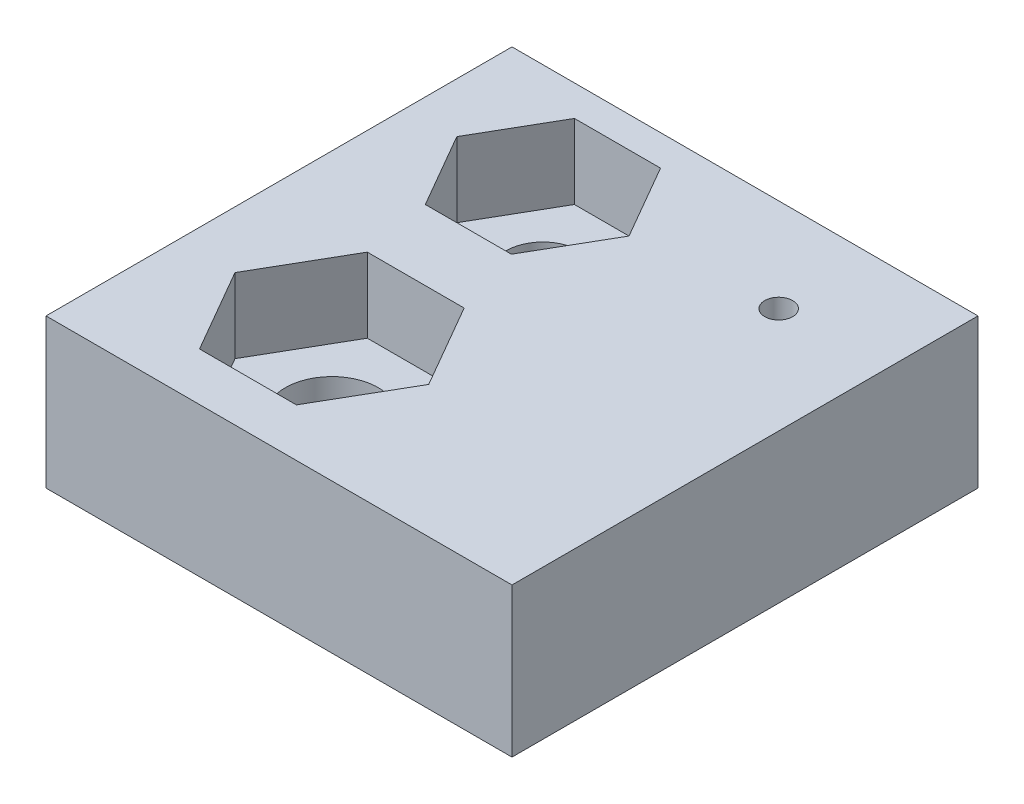
SolidWorks part; units mm, degrees
ref_plane "Front Plane" through (0, 0, 0) normal (0, 0, 1) x (1, 0, 0)
ref_plane "Top Plane" through (0, 0, 0) normal (0, 1, 0) x (1, 0, 0)
ref_plane "Right Plane" through (0, 0, 0) normal (1, 0, 0) x (0, 0, -1)
sketch "Sketch1" plane through (0, 0, 0) normal (0, 1, 0) x (1, 0, 0)
  line L1 (-12.5, -12.5) -> (12.5, -12.5)
  line L2 (-12.5, -12.5) -> (-12.5, 12.5)
  line L3 (-12.5, 12.5) -> (12.5, 12.5)
  line L4 (12.5, -12.5) -> (12.5, 12.5)
  line L5 (-12.5, -12.5) -> (12.5, 12.5) construction
  line L6 (-12.5, 12.5) -> (12.5, -12.5) construction
  point P0 (0, 0)
  dimension "D1" = 25
  dimension "D2" = 25
extrude "Boss-Extrude1" add sketch "Sketch1" along normal blind 8
sketch "Sketch2" plane through (0, 8, 0) normal (0, 1, 0) x (1, 0, 0)
  circle A0 centre (-5.1912, 6.85) radius 2
  circle A1 centre (6.8147, 7.4919) radius 0.75
  circle A2 centre (-4.2474, -5.4178) radius 2.5
  point P4 (-13.0466, 7.2118)
  point P7 (-13.0466, 7.4919)
  point P8 (6.8147, 7.4919)
  point P9 (-5.6821, 7.4919)
  point P10 (-4.2474, -5.4178)
  dimension "D1" = 1.5
  dimension "4" = 4
  dimension "D2" = 5
extrude "Cut-Extrude1" cut sketch "Sketch2" against normal blind 8
sketch "Sketch3" plane through (0, 8, 0) normal (0, 1, 0) x (1, 0, 0)
  line L1 (-0.5724, 6.85) -> (-2.8818, 10.85)
  line L2 (-2.8818, 10.85) -> (-7.5006, 10.85)
  line L3 (-7.5006, 10.85) -> (-9.8101, 6.85)
  line L4 (-9.8101, 6.85) -> (-7.5006, 2.85)
  line L5 (-7.5006, 2.85) -> (-2.8818, 2.85)
  line L6 (-2.8818, 2.85) -> (-0.5724, 6.85)
  line L7 (0.9488, -5.4178) -> (-1.6493, -0.9178)
  line L8 (-1.6493, -0.9178) -> (-6.8455, -0.9178)
  line L9 (-6.8455, -0.9178) -> (-9.4435, -5.4178)
  line L10 (-9.4435, -5.4178) -> (-6.8455, -9.9178)
  line L11 (-6.8455, -9.9178) -> (-1.6493, -9.9178)
  line L12 (-1.6493, -9.9178) -> (0.9488, -5.4178)
  circle A0 centre (-5.1912, 6.85) radius 4 construction
  circle A1 centre (-4.2474, -5.4178) radius 4.5 construction
  dimension "D1" = 8
  dimension "D2" = 9
extrude "Cut-Extrude2" cut sketch "Sketch3" against normal blind 4
